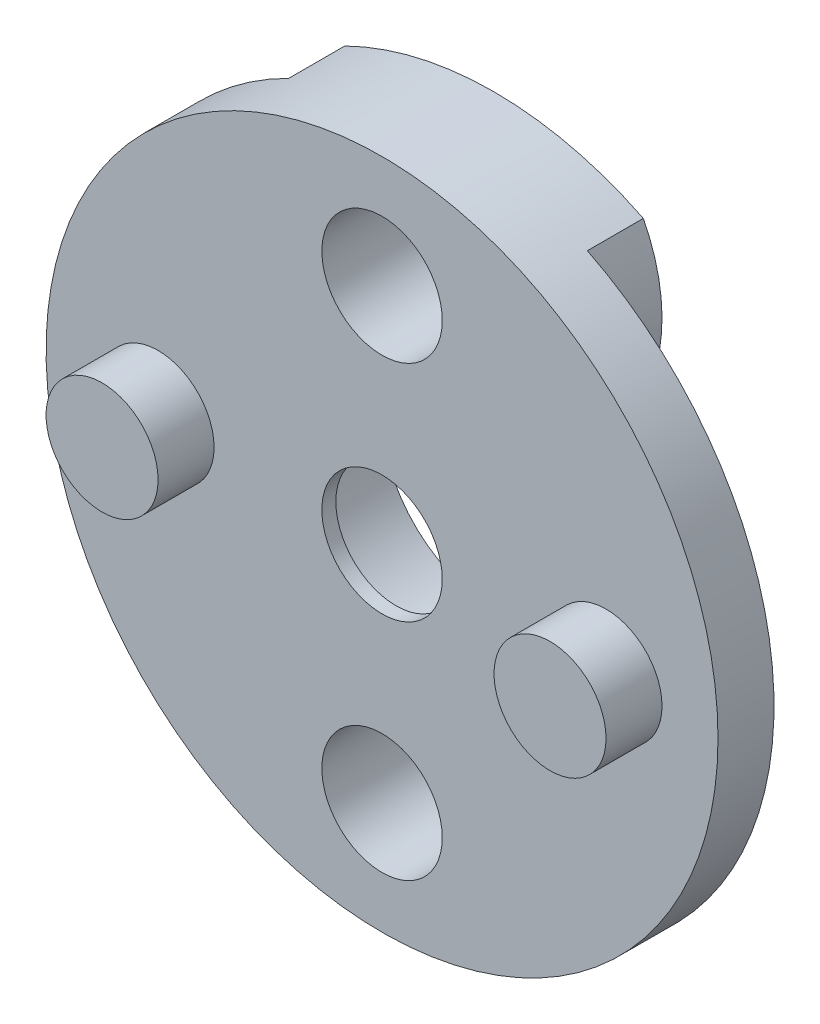
SolidWorks part; units mm, degrees
ref_plane "Front Plane" through (0, 0, 0) normal (0, 0, 1) x (1, 0, 0)
ref_plane "Top Plane" through (0, 0, 0) normal (0, 1, 0) x (1, 0, 0)
ref_plane "Right Plane" through (0, 0, 0) normal (1, 0, 0) x (0, 0, -1)
sketch "Sketch1" plane through (0, 0, 0) normal (0, 0, 1) x (1, 0, 0)
  circle A0 centre (0, 0) radius 12
  dimension "D1" = 24
extrude "Boss-Extrude1" add sketch "Sketch1" along normal blind 2
sketch "Sketch2" plane through (0, 0, 2) normal (0, 0, 1) x (1, 0, 0)
  line L0 (-8, 0) -> (8, 0) construction
  circle A0 centre (-8, 0) radius 2
  circle A1 centre (8, 0) radius 2
  dimension "D1" = 16
  dimension "D2" = 4
extrude "Boss-Extrude2" add sketch "Sketch2" along normal blind 2
hole_wizard "Ø4.3 (4.3) Diameter Hole1" positions "Sketch3" profile "Sketch4" hole size "Ø4.3" standard "JIS" end condition through all
sketch "Sketch3" plane through (0, 0, 2) normal (0, 0, 1) x (1, 0, 0)
  point P0 (0, 8)
  point P2 (0, 0)
  point P5 (0, -8)
  dimension "D1" = 16
  dimension "D2" = 8
sketch "Sketch4" plane through (0, 8, 2) normal (1, 0, 0) x (0, -1, 0)
  line L0 (0, 0) -> (0, 2)
  line L1 (0, 2) -> (2.15, 2)
  line L2 (2.15, 2) -> (2.15, 0)
  line L5 (2.15, 0) -> (0, 0)
  line L11 (0, -6.35) -> (0, 107.95) construction
  dimension "Thru Hole Dia." = 4.3
  dimension "Thru Hole Depth" = 2
sketch "Sketch5" plane through (0, 0, 0) normal (0, 0, -1) x (-1, 0, 0)
  arc A0 (4.4721, -4) -> (4.4721, 4) centre (0, 0) ccw
  arc A1 (4.4721, 4) -> (5.3327, 10.75) centre (0, 8) ccw
  arc A2 (5.3327, -10.75) -> (4.4721, -4) centre (0, -8) ccw
  arc A3 (5.3327, 10.75) -> (-5.3327, 10.75) centre (0, 0) ccw
  arc A4 (-4.4721, -4) -> (-5.3327, -10.75) centre (0, -8) ccw
  arc A5 (-4.4721, 4) -> (-4.4721, -4) centre (0, 0) ccw
  arc A6 (-5.3327, 10.75) -> (-4.4721, 4) centre (0, 8) ccw
  circle A7 centre (0, 0) radius 12 construction
  arc A8 (-5.3327, -10.75) -> (5.3327, -10.75) centre (0, 0) ccw
  circle A9 centre (0, 8) radius 2.15 construction
  circle A10 centre (0, -8) radius 2.15 construction
  circle A11 centre (0, 8) radius 2.15
  circle A12 centre (0, -8) radius 2.15
  circle A13 centre (0, 0) radius 4
  dimension "D1" = 12
  dimension "D2" = 8
extrude "Boss-Extrude3" add sketch "Sketch5" along normal blind 2
sketch "Sketch6" plane through (0, 0, 0) normal (0, 0, -1) x (-1, 0, 0)
  circle A1 centre (0, 0) radius 4
  circle A2 centre (0, 0) radius 4
  dimension "D1" = 0
extrude "Cut-Extrude1" cut sketch "Sketch6" against normal blind 1.5
equation "\"D2@Sketch3\"=\"D1@Sketch3\"/2"
